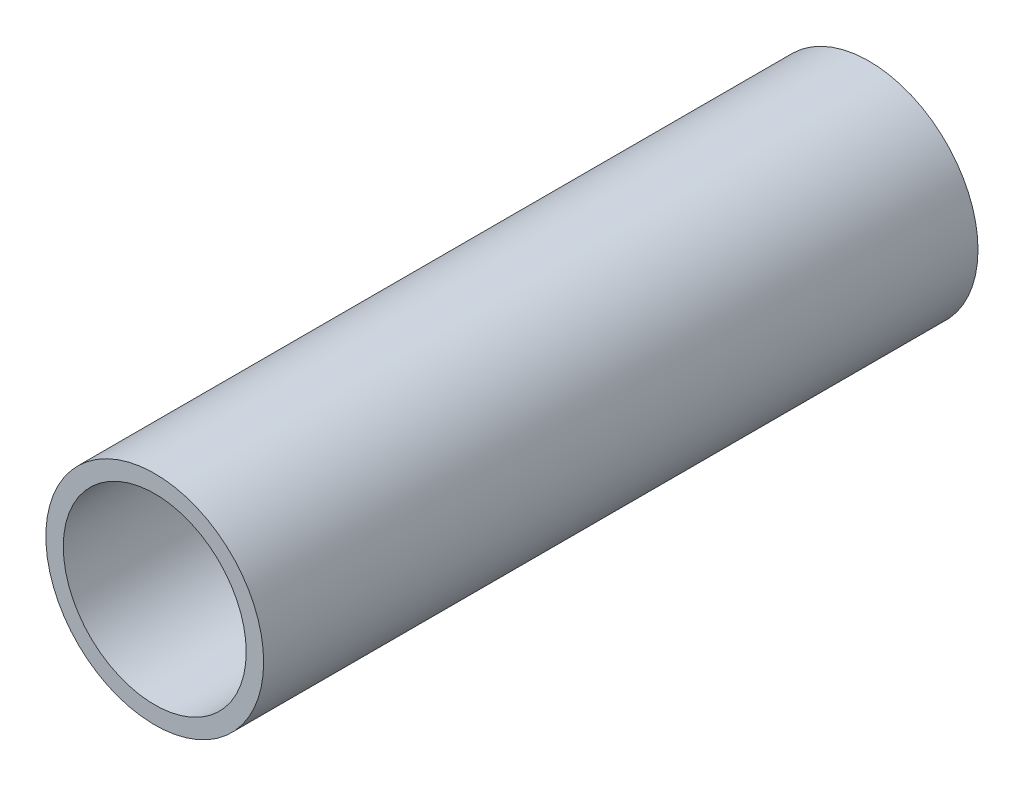
SolidWorks part; units mm, degrees
ref_plane "Piano frontale" through (0, 0, 0) normal (0, 0, 1) x (1, 0, 0)
ref_plane "Piano superiore" through (0, 0, 0) normal (0, 1, 0) x (1, 0, 0)
ref_plane "Piano destro" through (0, 0, 0) normal (1, 0, 0) x (0, 0, -1)
sketch "Schizzo1" plane through (0, 0, 0) normal (0, 0, 1) x (1, 0, 0)
  circle A0 centre (0, 0) radius 10.5
  circle A1 centre (0, 0) radius 12.5
  dimension "D1" = 25
  dimension "D2" = 21
extrude "Estrusione-Estrusione1" add sketch "Schizzo1" along normal blind 82
